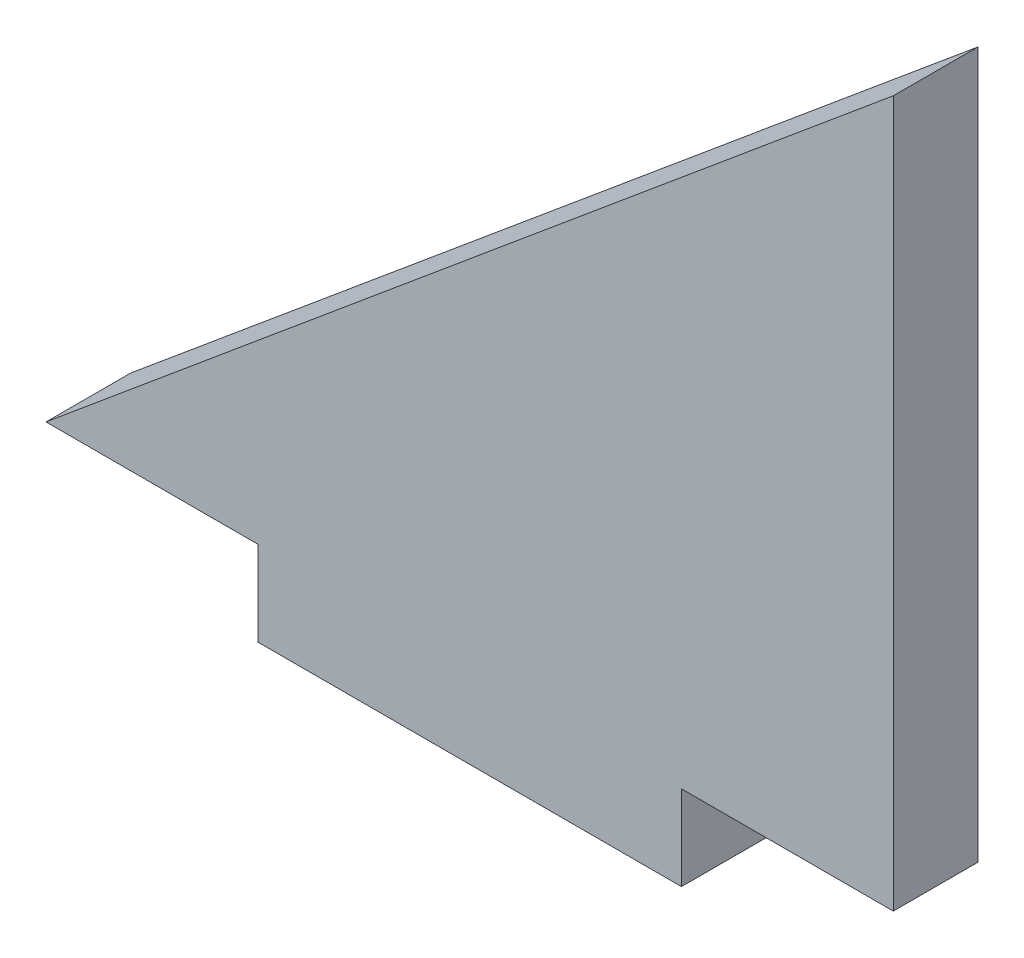
SolidWorks part; units mm, degrees
ref_plane "Front Plane" through (0, 0, 0) normal (0, 0, 1) x (1, 0, 0)
ref_plane "Top Plane" through (0, 0, 0) normal (0, 1, 0) x (1, 0, 0)
ref_plane "Right Plane" through (0, 0, 0) normal (1, 0, 0) x (0, 0, -1)
sketch "Sketch2" plane through (0, 0, 0) normal (0, 0, 1) x (1, 0, 0)
  line L0 (0, 0) -> (-7.5, 0)
  line L1 (-30, 0) -> (0, 25)
  line L2 (0, 25) -> (0, 0)
  line L3 (-22.5, 0) -> (-30, 0)
  line L5 (-22.5, 0) -> (-22.5, -3)
  line L6 (-22.5, -3) -> (-7.5, -3)
  line L7 (-7.5, 0) -> (-7.5, -3)
  dimension "D1" = 25
  dimension "D2" = 30
  dimension "D3" = 3
  dimension "D4" = 15
  dimension "D5" = 7.5
extrude "Boss-Extrude1" add sketch "Sketch2" along normal mid plane 3
